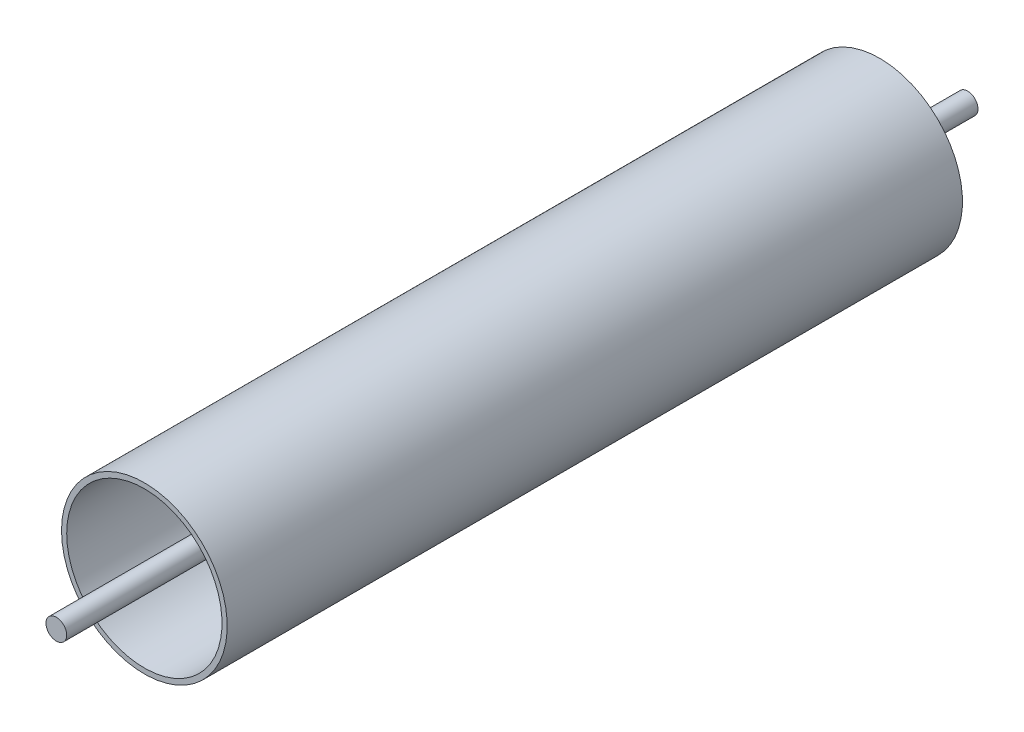
SolidWorks part; units mm, degrees
ref_plane "Front Plane" through (0, 0, 0) normal (0, 0, 1) x (1, 0, 0)
ref_plane "Top Plane" through (0, 0, 0) normal (0, 1, 0) x (1, 0, 0)
ref_plane "Right Plane" through (0, 0, 0) normal (1, 0, 0) x (0, 0, -1)
sketch "Sketch1" plane through (0, 0, 0) normal (0, 0, 1) x (1, 0, 0)
  circle A0 centre (0, 0) radius 3.175
extrude "Boss-Extrude1" add sketch "Sketch1" along normal mid plane 279.4 contours A0
sketch "Sketch2" plane through (0, 0, 0) normal (0, 0, 1) x (1, 0, 0)
  circle A0 centre (0, 0) radius 23.8125
  circle A1 centre (0, 0) radius 25.4
extrude "Boss-Extrude2" add sketch "Sketch2" along normal mid plane 225.425
